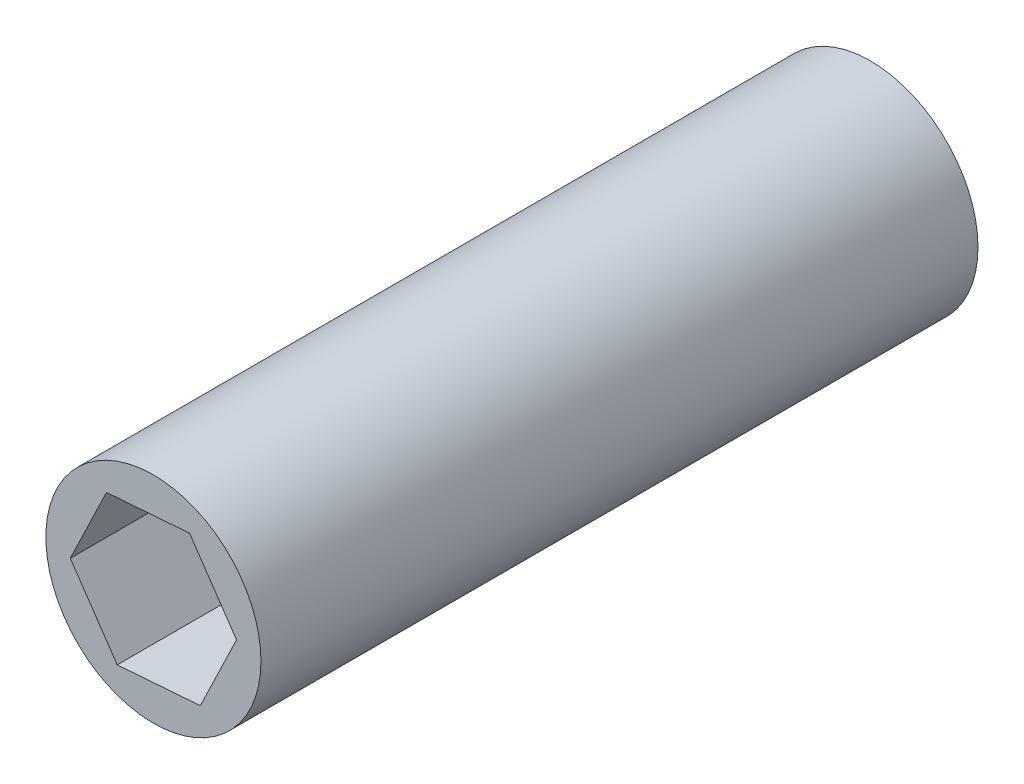
SolidWorks part; units mm, degrees
ref_plane "Front Plane" through (0, 0, 0) normal (0, 0, 1) x (1, 0, 0)
ref_plane "Top Plane" through (0, 0, 0) normal (0, 1, 0) x (1, 0, 0)
ref_plane "Right Plane" through (0, 0, 0) normal (1, 0, 0) x (0, 0, -1)
sketch "Sketch1" plane through (0, 0, 0) normal (0, 0, 1) x (1, 0, 0)
  circle A0 centre (0, 0) radius 1.5
extrude "Boss-Extrude1" add sketch "Sketch1" along normal blind 10
sketch "Sketch2" plane through (0, 0, 10) normal (0, 0, 1) x (1, 0, 0)
  line L1 (0.6544, -0.9605) -> (1.159, 0.0865)
  line L2 (1.159, 0.0865) -> (0.5046, 1.047)
  line L3 (0.5046, 1.047) -> (-0.6544, 0.9605)
  line L4 (-0.6544, 0.9605) -> (-1.159, -0.0865)
  line L5 (-1.159, -0.0865) -> (-0.5046, -1.047)
  line L6 (-0.5046, -1.047) -> (0.6544, -0.9605)
  circle A0 centre (0, 0) radius 1.0065 construction
extrude "Cut-Extrude1" cut sketch "Sketch2" against normal blind 3
